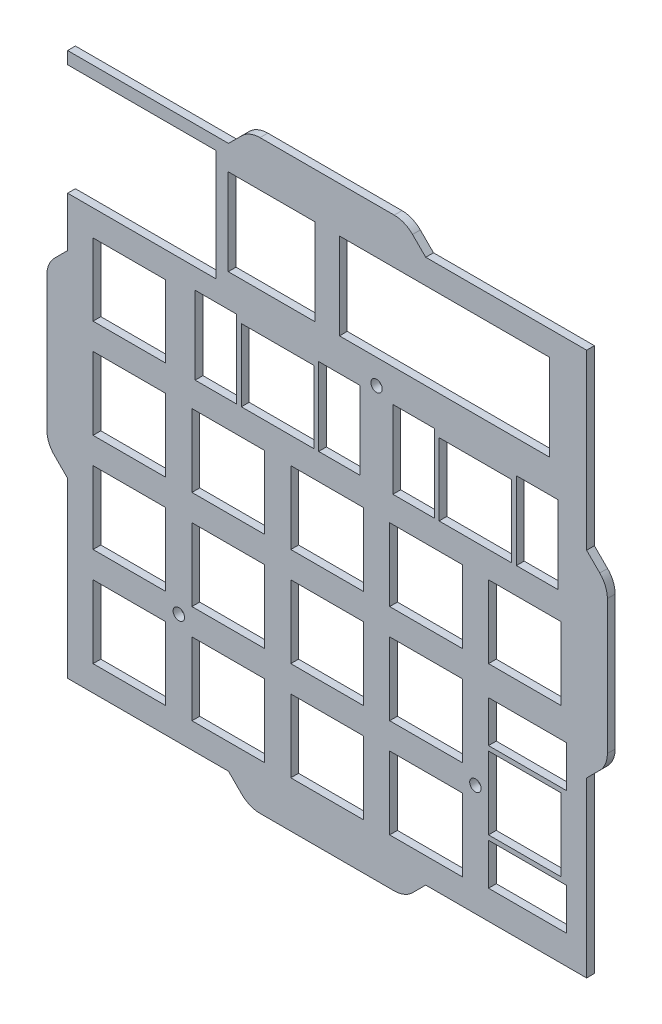
SolidWorks part; units mm, degrees
ref_plane "Front Plane" through (0, 0, 0) normal (1, 0, 0) x (0, 1, 0)
ref_plane "Top Plane" through (0, 0, 0) normal (0, 0, 1) x (0, 1, 0)
ref_plane "Right Plane" through (0, 0, 0) normal (0, 1, 0) x (-1, 0, 0)
sketch "Sketch2" plane through (0, 0, 0) normal (0, 0, 1) x (0, 1, 0)
  line L0 (0.0954, 95.5094) -> (76.2988, 95.5094) construction
  line L1 (76.2988, 95.5094) -> (76.2988, 76.4594) construction
  line L2 (76.2988, 0.2594) -> (0.0954, 0.2594) construction
  line L3 (0.0954, 0.2594) -> (0.0954, 95.5094) construction
  line L20 (12.1454, 16.7838) -> (12.1454, 2.7838)
  line L21 (12.1454, 2.7838) -> (26.1454, 2.7838)
  line L22 (26.1454, 2.7838) -> (26.1454, 16.7838)
  line L39 (26.1454, 16.7838) -> (12.1454, 16.7838)
  line L40 (40.7217, 16.7838) -> (54.7216, 16.7838)
  line L41 (54.7216, 16.7838) -> (54.7216, 2.7838)
  line L42 (54.7216, 2.7838) -> (40.7217, 2.7838)
  line L43 (40.7217, 2.7838) -> (40.7217, 16.7838)
  line L54 (59.7727, 26.3094) -> (59.7727, 12.3094)
  line L71 (59.7727, 12.3094) -> (73.6711, 12.3094)
  line L72 (73.6711, 12.3094) -> (73.6711, 26.3094)
  line L73 (73.6711, 26.3094) -> (59.7727, 26.3094)
  line L80 (2.6198, 35.8339) -> (16.62, 35.8339)
  line L81 (16.62, 35.8339) -> (16.62, 21.8347)
  line L82 (16.62, 21.8347) -> (2.6198, 21.8347)
  line L83 (2.6198, 21.8347) -> (2.6198, 35.8339)
  line L84 (21.6708, 35.8339) -> (35.6708, 35.8339)
  line L85 (35.6708, 35.8339) -> (35.6708, 21.8347)
  line L86 (35.6708, 21.8347) -> (21.6708, 21.8347)
  line L87 (21.6708, 21.8347) -> (21.6708, 35.8339)
  line L88 (40.7217, 35.8339) -> (54.7216, 35.8339)
  line L89 (54.7216, 35.8339) -> (54.7216, 21.8347)
  line L90 (54.7216, 21.8347) -> (40.7217, 21.8347)
  line L91 (40.7217, 21.8347) -> (40.7217, 35.8339)
  line L92 (2.6198, 54.8839) -> (16.62, 54.8839)
  line L93 (16.62, 54.8839) -> (16.62, 40.8849)
  line L94 (16.62, 40.8849) -> (2.6198, 40.8849)
  line L95 (2.6198, 40.8849) -> (2.6198, 54.8839)
  line L96 (21.6708, 54.8839) -> (35.6708, 54.8839)
  line L97 (35.6708, 54.8839) -> (35.6708, 40.8849)
  line L98 (35.6708, 40.8849) -> (21.6708, 40.8849)
  line L99 (21.6708, 40.8849) -> (21.6708, 54.8839)
  line L100 (40.7217, 54.8839) -> (54.7216, 54.8839)
  line L101 (54.7216, 54.8839) -> (54.7216, 40.8849)
  line L102 (54.7216, 40.8849) -> (40.7217, 40.8849)
  line L103 (40.7217, 40.8849) -> (40.7217, 54.8839)
  line L114 (59.7727, 64.4094) -> (59.7727, 50.4094)
  line L131 (59.7727, 50.4094) -> (73.6711, 50.4094)
  line L132 (73.6711, 50.4094) -> (73.6711, 64.4094)
  line L133 (73.6711, 64.4094) -> (59.7727, 64.4094)
  line L140 (2.6198, 73.9309) -> (16.62, 73.9309)
  line L141 (16.62, 73.9309) -> (16.62, 59.9368)
  line L142 (16.62, 59.9368) -> (2.6198, 59.9368)
  line L143 (2.6198, 59.9368) -> (2.6198, 73.9309)
  line L144 (21.6708, 73.9309) -> (35.6708, 73.9309)
  line L145 (35.6708, 73.9309) -> (35.6708, 59.9368)
  line L146 (35.6708, 59.9368) -> (21.6708, 59.9368)
  line L147 (21.6708, 59.9368) -> (21.6708, 73.9309)
  line L148 (40.7217, 73.9309) -> (54.7216, 73.9309)
  line L149 (54.7216, 73.9309) -> (54.7216, 59.9368)
  line L150 (54.7216, 59.9368) -> (40.7217, 59.9368)
  line L151 (40.7217, 59.9368) -> (40.7217, 73.9309)
  line L152 (2.6198, 92.9878) -> (16.62, 92.9878)
  line L153 (16.62, 92.9878) -> (16.62, 78.9878)
  line L154 (16.62, 78.9878) -> (2.6198, 78.9878)
  line L155 (2.6198, 78.9878) -> (2.6198, 92.9878)
  line L156 (21.6708, 92.9878) -> (35.6708, 92.9878)
  line L157 (35.6708, 92.9878) -> (35.6708, 78.9878)
  line L158 (35.6708, 78.9878) -> (21.6708, 78.9878)
  line L159 (21.6708, 78.9878) -> (21.6708, 92.9878)
  line L160 (40.7217, 92.9878) -> (54.7216, 92.9878)
  line L161 (54.7216, 92.9878) -> (54.7216, 78.9878)
  line L162 (54.7216, 78.9878) -> (40.7217, 78.9878)
  line L163 (40.7217, 78.9878) -> (40.7217, 92.9878)
  line L164 (59.7727, 92.9878) -> (73.6711, 92.9878)
  line L165 (73.6711, 92.9878) -> (73.6711, 78.9878)
  line L166 (73.6711, 78.9878) -> (59.7727, 78.9878)
  line L167 (59.7727, 78.9878) -> (59.7727, 92.9878)
  line L168 (76.2988, 95.5094) -> (102.4915, 95.5094) construction
  line L169 (76.2988, 0.2594) -> (102.4915, 0.2594) construction
  line L170 (102.4915, 0.2594) -> (102.4915, 95.5094) construction
  line L172 (19.1454, 95.5094) -> (19.1454, 0.2594) construction
  line L173 (0.0954, 76.4594) -> (76.2988, 76.4594) construction
  line L174 (0.0954, 57.4094) -> (76.2988, 57.4094) construction
  line L175 (0.0954, 38.3594) -> (76.2988, 38.3594) construction
  line L176 (0.0954, 19.3094) -> (76.2988, 19.3094) construction
  line L177 (38.1971, 95.5094) -> (38.1971, 0.2594) construction
  line L178 (57.2471, 95.5094) -> (57.2471, 0.2594) construction
  line L179 (76.2988, 45.5031) -> (81.0613, 45.5031) construction
  line L180 (81.0613, 66.9344) -> (97.73, 66.9344)
  line L181 (81.0613, 66.9344) -> (81.0613, 50.2656)
  line L182 (81.0613, 50.2656) -> (97.73, 50.2656)
  line L183 (97.73, 66.9344) -> (97.73, 50.2656)
  line L184 (81.0613, 45.5031) -> (81.0613, 5.0219)
  line L185 (81.0613, 5.0219) -> (97.73, 5.0219)
  line L186 (97.73, 5.0219) -> (97.73, 45.5031)
  line L187 (97.73, 45.5031) -> (81.0613, 45.5031)
  line L189 (78.68, 95.5094) -> (78.68, 69.3156)
  line L190 (78.68, 69.3156) -> (100.1103, 69.3156)
  line L191 (100.1103, 95.5636) -> (100.1103, 69.3156)
  line L194 (102.4915, 0.2594) -> (102.4915, 28.8844)
  line L195 (102.4915, 0.2594) -> (102.4915, -2.1219)
  line L196 (102.4915, -2.1219) -> (69.1029, -2.1219)
  line L197 (-2.2858, -2.1219) -> (-2.2858, 28.8844)
  line L198 (-2.2858, 97.8906) -> (31.1029, 97.8906)
  line L199 (78.68, 97.8906) -> (78.68, 95.5094)
  line L200 (100.1103, 95.5636) -> (100.1103, 97.8906)
  line L201 (100.1103, 97.8906) -> (102.4915, 97.8906)
  line L202 (102.4915, 97.8906) -> (102.4915, 95.5094)
  line L203 (35.0454, 1.7838) -> (27.0454, 1.7838)
  line L204 (3.2454, 16.7838) -> (11.2454, 16.7838)
  line L205 (3.2454, 16.7838) -> (3.2454, 1.7838)
  line L206 (3.2454, 1.7838) -> (11.2454, 1.7838)
  line L207 (11.2454, 16.7838) -> (11.2454, 1.7838)
  line L208 (27.0454, 16.7838) -> (27.0454, 1.7838)
  line L209 (35.0454, 16.7838) -> (27.0454, 16.7838)
  line L210 (35.0454, 16.7838) -> (35.0454, 1.7838)
  line L211 (59.7727, 35.2094) -> (74.7727, 35.2094)
  line L212 (59.7727, 11.4094) -> (74.7727, 11.4094)
  line L213 (59.7727, 11.4094) -> (59.7727, 3.4094)
  line L214 (59.7727, 3.4094) -> (74.7727, 3.4094)
  line L215 (74.7727, 11.4094) -> (74.7727, 3.4094)
  line L216 (74.7727, 27.2094) -> (74.7727, 35.2094)
  line L217 (59.7727, 27.2094) -> (74.7727, 27.2094)
  line L218 (59.7727, 27.2094) -> (59.7727, 35.2094)
  line L219 (59.7727, 41.5094) -> (74.7727, 41.5094)
  line L220 (59.7727, 65.3094) -> (74.7727, 65.3094)
  line L221 (59.7727, 65.3094) -> (59.7727, 73.3094)
  line L222 (59.7727, 73.3094) -> (74.7727, 73.3094)
  line L223 (74.7727, 65.3094) -> (74.7727, 73.3094)
  line L224 (74.7727, 49.5094) -> (74.7727, 41.5094)
  line L225 (59.7727, 49.5094) -> (74.7727, 49.5094)
  line L226 (59.7727, 49.5094) -> (59.7727, 41.5094)
  line L227 (7.2454, 16.7838) -> (19.1454, 16.7838) construction
  line L228 (59.7727, 7.4094) -> (59.7727, 19.3094) construction
  line L229 (59.7727, 57.4094) -> (59.7727, 69.3094) construction
  line L230 (76.2988, 38.3594) -> (76.2988, 0.2594) construction
  line L231 (76.2988, 76.4594) -> (76.2988, 38.3594) construction
  line L232 (50.1029, -2.1219) -> (50.1029, -6.1219) construction
  line L233 (63.0318, -6.1219) -> (37.1739, -6.1219)
  line L234 (66.5673, -4.6574) -> (69.1029, -2.1219)
  line L235 (33.6384, -4.6574) -> (31.1029, -2.1219)
  line L236 (31.1029, -2.1219) -> (-2.2858, -2.1219)
  line L237 (69.1029, -2.1219) -> (31.1029, -2.1219) construction
  line L238 (-2.2858, 47.8844) -> (102.4915, 47.8844) construction
  line L239 (50.1029, -2.1219) -> (50.1029, 97.8906) construction
  line L240 (50.1029, 97.8906) -> (50.1029, 101.8906) construction
  line L244 (31.1029, 97.8906) -> (69.1029, 97.8906) construction
  line L245 (69.1029, 97.8906) -> (78.68, 97.8906)
  line L246 (37.1739, 101.8906) -> (63.0318, 101.8906)
  line L247 (66.5673, 100.4261) -> (69.1029, 97.8906)
  line L248 (31.1029, 97.8906) -> (33.6384, 100.4261)
  line L249 (-2.2858, 47.8844) -> (-6.2858, 47.8844) construction
  line L250 (-6.2858, 60.8133) -> (-6.2858, 34.9554)
  line L251 (-4.8214, 31.4199) -> (-2.2858, 28.8844)
  line L252 (-4.8214, 64.3488) -> (-2.2858, 66.8844)
  line L253 (-2.2858, 28.8844) -> (-2.2858, 66.8844) construction
  line L254 (-2.2858, 66.8844) -> (-2.2858, 97.8906)
  line L255 (102.4915, 47.8844) -> (106.4915, 47.8844) construction
  line L256 (106.4915, 60.8133) -> (106.4915, 34.9554)
  line L257 (105.0271, 64.3488) -> (102.4915, 66.8844)
  line L258 (102.4915, 66.8844) -> (102.4915, 95.5094)
  line L260 (105.0271, 31.4199) -> (102.4915, 28.8844)
  arc A0 (-6.2858, 34.9554) -> (-4.8214, 31.4199) centre (-1.2858, 34.9554) ccw
  arc A1 (-6.2858, 60.8133) -> (-4.8214, 64.3488) centre (-1.2858, 60.8133) cw
  arc A2 (37.1739, 101.8906) -> (33.6384, 100.4261) centre (37.1739, 96.8906) ccw
  arc A3 (63.0318, 101.8906) -> (66.5673, 100.4261) centre (63.0318, 96.8906) cw
  arc A4 (106.4915, 60.8133) -> (105.0271, 64.3488) centre (101.4915, 60.8133) ccw
  arc A5 (106.4915, 34.9554) -> (105.0271, 31.4199) centre (101.4915, 34.9554) cw
  arc A6 (37.1739, -6.1219) -> (33.6384, -4.6574) centre (37.1739, -1.1219) cw
  arc A7 (63.0318, -6.1219) -> (66.5673, -4.6574) centre (63.0318, -1.1219) ccw
  circle A8 centre (19.1454, 76.4594) radius 1.1
  circle A9 centre (19.1454, 19.3094) radius 1.1
  circle A10 centre (76.2988, 38.3594) radius 1.1
  point P11 (19.1454, 16.7838)
  point P36 (7.2454, 16.7838)
  point P38 (59.7727, 19.3094)
  point P39 (59.7727, 7.4094)
  point P40 (59.7727, 69.3094)
  point P41 (59.7727, 57.4094)
  point P55 (50.1029, -2.1219)
  point P60 (50.1029, -6.1219)
  point P69 (50.1029, 101.8906)
  point P77 (-6.2858, 47.8844)
  point P107 (106.4915, 47.8844)
  point P113 (102.4915, 62.8844)
  point P127 (35.1029, -6.1219)
  point P130 (65.1029, -6.1219)
  point P133 (19.1454, 19.3094)
  point P139 (21.6708, 47.8844)
  point P140 (0, 0)
  point P141 (0, 0)
  point P190 (76.2988, 45.5031)
  point P205 (73.6711, 57.4094)
  point P206 (73.6711, 19.3094)
  dimension "D34" = 5
  dimension "D35" = 2.2
  dimension "D36" = 2.2
  dimension "D37" = 2.2
  dimension "D3" = 19.05
  dimension "D7" = 19.05
  dimension "D8" = 19.05
  dimension "D9" = 19.05
  dimension "D10" = 19.05
  dimension "D11" = 19.0517
  dimension "D5" = 19.05
  dimension "D6" = 19.05
  dimension "D2" = 26.1928
  dimension "D12" = 7.1437
  dimension "D13" = 4.7625
  dimension "D14" = 16.6687
  dimension "D4" = 16.6687
  dimension "D15" = 4.7625
  dimension "D16" = 2.3813
  dimension "D17" = 2.3813
  dimension "D18" = 2.3813
  dimension "D19" = 2.3813
  dimension "D20" = 2.3813
  dimension "D21" = 2.3813
  dimension "D22" = 7.1437
  dimension "D23" = 14
  dimension "D24" = 14
  dimension "D25" = 2.5244
  dimension "D26" = 14
  dimension "D28" = 8
  dimension "D27" = 11.9
  dimension "D29" = 15
  dimension "D32" = 30
  dimension "D33" = 4
  dimension "D30" = 225
  dimension "D31" = 225
extrude "Boss-Extrude1" add sketch "Sketch2" along normal blind 1.5
equation "\"D19@Sketch2\"=2.38125"
equation "\"D20@Sketch2\"=2.38125"
equation "\"D21@Sketch2\"=2.38125"
